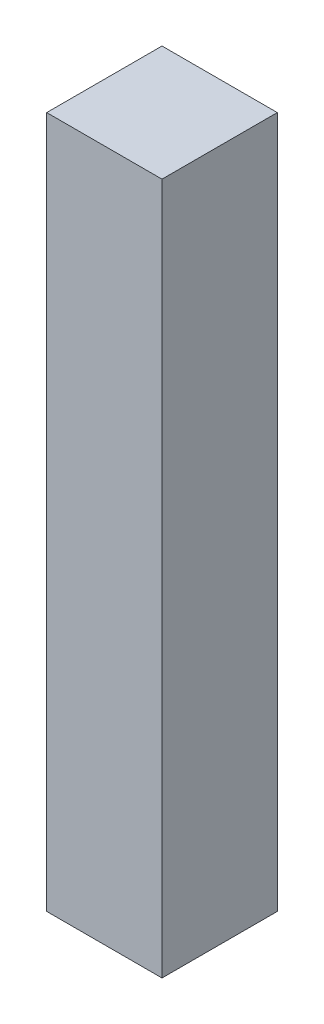
SolidWorks part; units mm, degrees
ref_plane "Front Plane" through (0, 0, 0) normal (0, 0, 1) x (1, 0, 0)
ref_plane "Top Plane" through (0, 0, 0) normal (0, 1, 0) x (1, 0, 0)
ref_plane "Right Plane" through (0, 0, 0) normal (1, 0, 0) x (0, 0, -1)
sketch "Sketch1" plane through (0, 0, 0) normal (0, 1, 0) x (1, 0, 0)
  line L1 (2.5, -2.5) -> (-2.5, -2.5)
  line L2 (2.5, -2.5) -> (2.5, 2.5)
  line L3 (2.5, 2.5) -> (-2.5, 2.5)
  line L4 (-2.5, -2.5) -> (-2.5, 2.5)
  line L5 (2.5, -2.5) -> (-2.5, 2.5) construction
  line L6 (2.5, 2.5) -> (-2.5, -2.5) construction
  point P0 (0, 0)
  dimension "D1" = 5
extrude "Boss-Extrude1" add sketch "Sketch1" along normal mid plane 30
